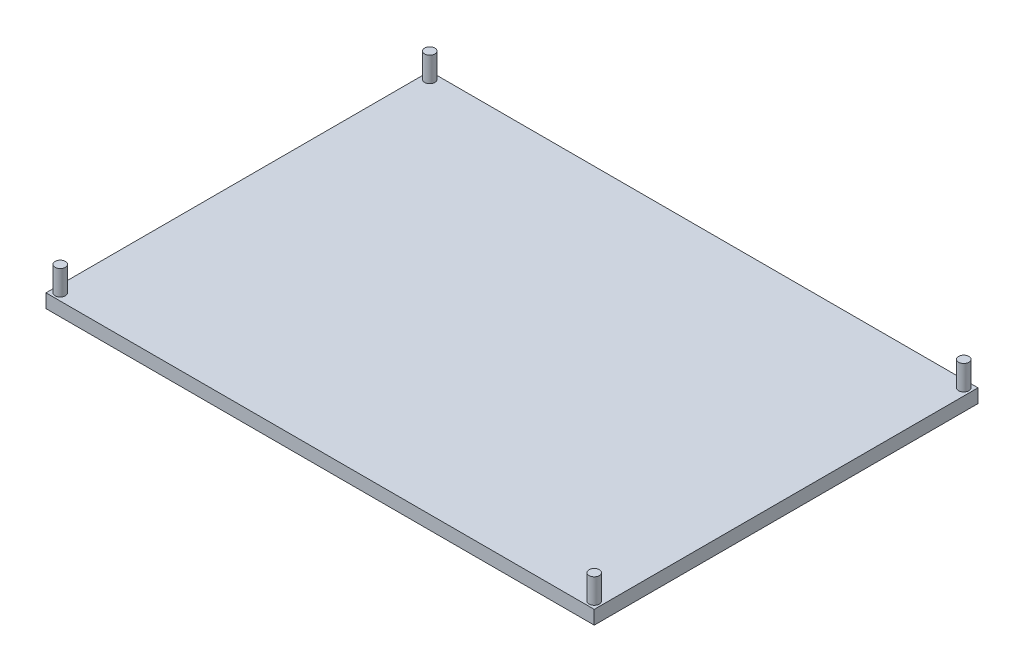
SolidWorks part; units mm, degrees
ref_plane "Front Plane" through (0, 0, 0) normal (0, 0, 1) x (1, 0, 0)
ref_plane "Top Plane" through (0, 0, 0) normal (0, 1, 0) x (1, 0, 0)
ref_plane "Right Plane" through (0, 0, 0) normal (1, 0, 0) x (0, 0, -1)
sketch "Sketch1" plane through (0, 0, 0) normal (0, 1, 0) x (1, 0, 0)
  line L1 (-127, -88.9) -> (127, -88.9)
  line L2 (-127, -88.9) -> (-127, 88.9)
  line L3 (-127, 88.9) -> (127, 88.9)
  line L4 (127, -88.9) -> (127, 88.9)
  line L5 (-127, -88.9) -> (127, 88.9) construction
  line L6 (-127, 88.9) -> (127, -88.9) construction
  point P0 (0, 0)
  dimension "D1" = 254
  dimension "D2" = 177.8
extrude "Boss-Extrude1" add sketch "Sketch1" along normal blind 6.35
sketch "Sketch2" plane through (0, 6.35, 0) normal (0, 1, 0) x (1, 0, 0)
  line L0 (127, 88.9) -> (-127, 88.9) construction
  line L1 (-127, 88.9) -> (-127, -88.9) construction
  line L2 (127, -88.9) -> (127, 88.9) construction
  line L3 (-127, -88.9) -> (127, -88.9) construction
  circle A0 centre (-123.698, -85.598) radius 2.3813
  circle A1 centre (-123.698, 85.598) radius 2.3813
  circle A2 centre (123.698, 85.598) radius 2.3813
  circle A3 centre (123.698, -85.598) radius 2.3813
  point P0 (-123.698, 85.598)
  point P5 (123.698, 85.598)
  point P8 (123.698, -85.598)
  point P11 (-123.698, -85.598)
  dimension "D9" = 4.7625
  dimension "D10" = 4.7625
  dimension "D11" = 4.7625
  dimension "D12" = 4.7625
  dimension "D1" = 3.302
  dimension "D2" = 3.302
  dimension "D3" = 3.302
  dimension "D4" = 3.302
  dimension "D5" = 3.302
  dimension "D6" = 3.302
  dimension "D7" = 3.302
  dimension "D8" = 3.302
extrude "Boss-Extrude2" add sketch "Sketch2" along normal blind 11.43 contours A0 | A3 | A2 | A1
sketch "Sketch6" plane through (0, 0, 0) normal (0, -1, 0) x (1, 0, 0)
  line L0 (-127, 88.9) -> (127, 88.9) construction
  line L1 (0, 66.4765) -> (-98.99, 66.4765)
  line L2 (0, 66.4765) -> (0, 30.8567)
  line L3 (0, 30.8567) -> (-98.99, 30.8567)
  line L4 (-98.99, 66.4765) -> (-98.99, 30.8567)
  line L5 (-127, -88.9) -> (-127, 88.9) construction
  line L6 (127, 88.9) -> (127, -88.9) construction
  line L7 (93.6056, 56.5361) -> (53.0155, 56.5361)
  line L8 (93.6056, 56.5361) -> (93.6056, 53.2226)
  line L9 (93.6056, 53.2226) -> (53.0155, 53.2226)
  line L10 (53.0155, 56.5361) -> (53.0155, 53.2226)
  line L11 (93.6056, 56.5361) -> (53.0155, 53.2226) construction
  line L12 (93.6056, 53.2226) -> (53.0155, 56.5361) construction
  line L14 (-31.1441, -11.941) -> (-72.4254, -11.941)
  line L15 (-31.1441, -11.941) -> (-31.1441, -51.9118)
  line L16 (-31.1441, -51.9118) -> (-72.4254, -51.9118)
  line L17 (-72.4254, -11.941) -> (-72.4254, -51.9118)
  line L18 (-31.1441, -11.941) -> (-72.4254, -51.9118) construction
  line L19 (-31.1441, -51.9118) -> (-72.4254, -11.941) construction
  line L20 (127, -88.9) -> (-127, -88.9) construction
  point P8 (73.3106, 54.8794)
  point P15 (-51.7847, -31.9264)
  point P22 (-33.1098, -88.9)
  point P23 (-38.0243, -51.9118)
  dimension "D1" = 98.99
  dimension "D2" = 35.6198
  dimension "D3" = 22.4235
  dimension "D4" = 28.01
  dimension "D5" = 40.59
  dimension "D6" = 3.3135
  dimension "D7" = 33.3944
  dimension "D8" = 32.3639
  dimension "D9" = 39.9708
  dimension "D10" = 41.2814
  dimension "D11" = 75.2153
  dimension "D12" = 36.9882
